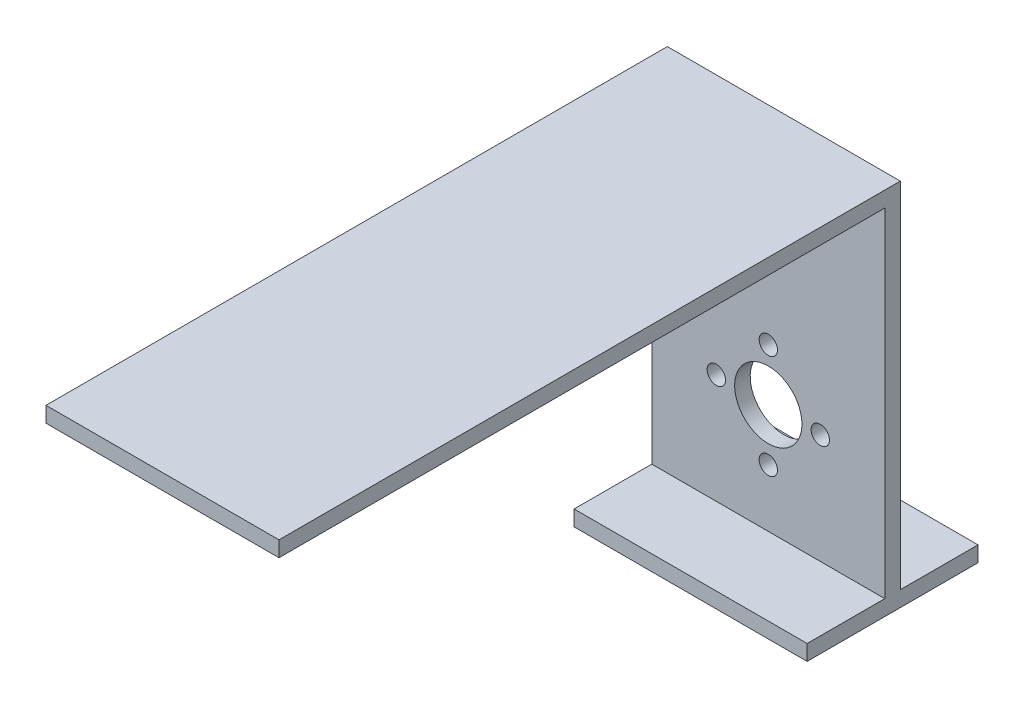
SolidWorks part; units mm, degrees
ref_plane "Front Plane" through (0, 0, 0) normal (0, 0, 1) x (1, 0, 0)
ref_plane "Top Plane" through (0, 0, 0) normal (0, 1, 0) x (1, 0, 0)
ref_plane "Right Plane" through (0, 0, 0) normal (1, 0, 0) x (0, 0, -1)
sketch "Sketch1" plane through (0, 0, 0) normal (1, 0, 0) x (0, 0, -1)
  line L0 (-99.06, 57.86) -> (-99.06, 55.32)
  line L1 (-99.06, 55.32) -> (0, 55.32)
  line L2 (0, 55.32) -> (0, 0)
  line L4 (-99.06, 57.86) -> (2.54, 57.86)
  line L5 (2.54, 57.86) -> (2.54, 0)
  line L6 (0, 0) -> (-12.7, 0)
  line L7 (-12.7, 0) -> (-12.7, -2.54)
  line L8 (-12.7, -2.54) -> (15.24, -2.54)
  line L9 (15.24, -2.54) -> (15.24, 0)
  line L10 (15.24, 0) -> (2.54, 0)
  point P11 (-48.26, 57.86)
  dimension "D1" = 2.54
  dimension "D2" = 2.54
  dimension "D3" = 2.54
  dimension "D4" = 60.4
  dimension "D5" = 12.7
  dimension "D6" = 12.7
  dimension "D7" = 101.6
extrude "Boss-Extrude1" add sketch "Sketch1" along normal blind 38.1
sketch "Sketch2" plane through (0, 0, 0) normal (0, 0, 1) x (1, 0, 0)
  line L0 (46.3162, 29.92) -> (-10.789, 29.92) construction
  line L2 (19.05, 36.7846) -> (19.05, -17.6164) construction
  line L3 (38.1, 0) -> (38.1, 57.86) construction
  line L4 (0, 0) -> (0, 57.86) construction
  line L5 (46.3162, 27.92) -> (-10.789, 27.92) construction
  line L6 (46.3162, 7.92) -> (-10.789, 7.92) construction
  line L7 (29.05, 36.7846) -> (29.05, -17.6164) construction
  line L8 (9.05, 36.7846) -> (9.05, -17.6164) construction
  line L9 (46.3162, 17.92) -> (-10.789, 17.92) construction
  line L10 (29.05, 17.92) -> (9.05, 17.92) construction
  circle A0 centre (19.05, 26.42) radius 1.5
  circle A1 centre (19.05, 9.42) radius 1.5
  circle A2 centre (27.55, 17.92) radius 1.5
  circle A3 centre (10.55, 17.92) radius 1.5
  circle A4 centre (19.05, 17.92) radius 5.5
  point P30 (0, 0)
  dimension "D6" = 3
  dimension "D7" = 3
  dimension "D9" = 3
  dimension "D10" = 3
  dimension "D11" = 11
  dimension "D2" = 20
  dimension "D3" = 10
  dimension "D4" = 10
  dimension "D5" = 2
  dimension "D8" = 10
  dimension "D12" = 0
extrude "Cut-Extrude2" cut sketch "Sketch2" against normal up to next
